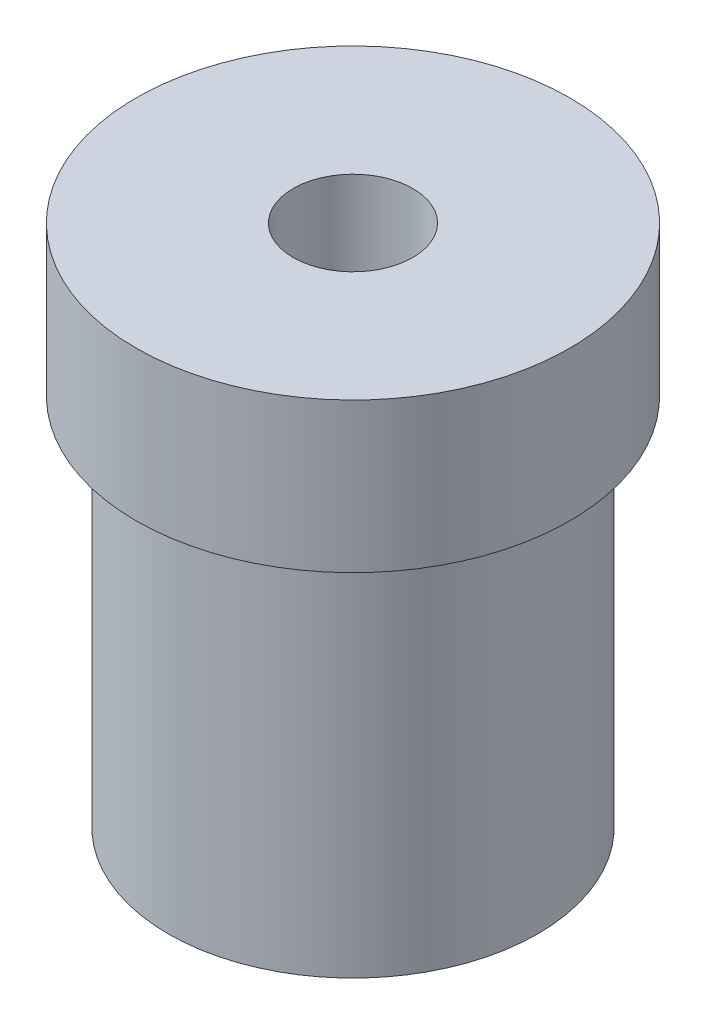
SolidWorks part; units mm, degrees
ref_plane "Спереди" through (0, 0, 0) normal (0, 0, 1) x (1, 0, 0)
ref_plane "Сверху" through (0, 0, 0) normal (0, 1, 0) x (1, 0, 0)
ref_plane "Справа" through (0, 0, 0) normal (1, 0, 0) x (0, 0, -1)
sketch "Sketch1" plane through (0, 0, 0) normal (0, 1, 0) x (1, 0, 0)
  circle A0 centre (0, 0) radius 12.35
  dimension "D1" = 24.7
extrude "Boss-Extrude1" add sketch "Sketch1" along normal blind 25
sketch "Sketch2" plane through (0, 25, 0) normal (0, 1, 0) x (1, 0, 0)
  circle A0 centre (0, 0) radius 14.5
  dimension "D1" = 29
extrude "Boss-Extrude2" add sketch "Sketch2" along normal blind 10
sketch "Sketch3" plane through (0, 35, 0) normal (0, 1, 0) x (1, 0, 0)
  circle A0 centre (0, 0) radius 4
  dimension "D1" = 8
extrude "Cut-Extrude1" cut sketch "Sketch3" against normal through all and the other way through all
